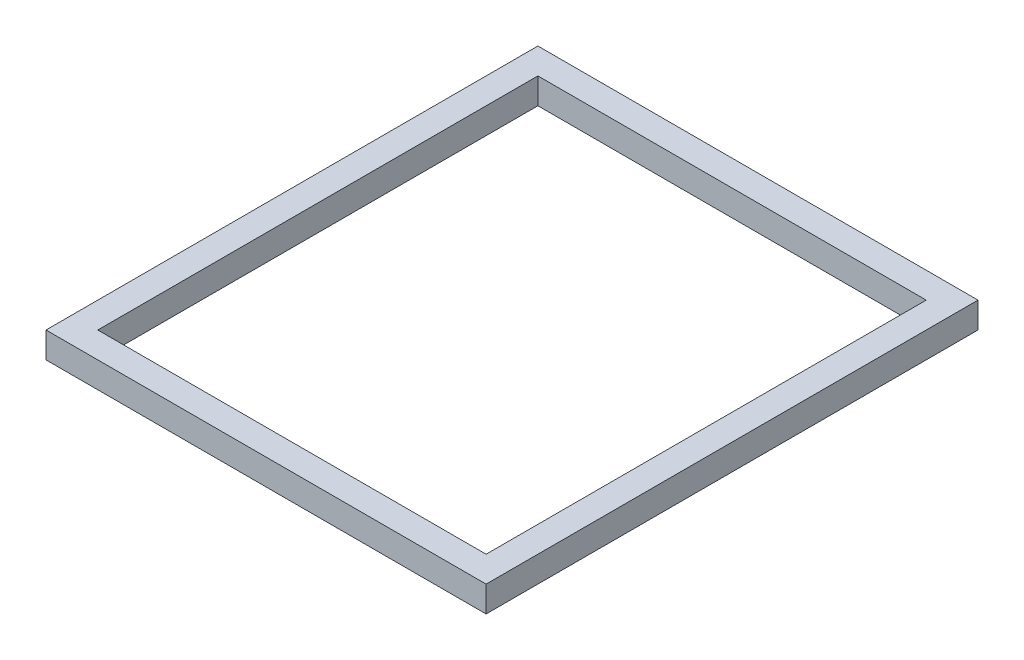
SolidWorks part; units mm, degrees
ref_plane "Front Plane" through (0, 0, 0) normal (0, 0, 1) x (1, 0, 0)
ref_plane "Top Plane" through (0, 0, 0) normal (0, 1, 0) x (1, 0, 0)
ref_plane "Right Plane" through (0, 0, 0) normal (1, 0, 0) x (0, 0, -1)
sketch "Sketch1" plane through (0, 0, 0) normal (0, 1, 0) x (1, 0, 0)
  line L1 (-53.975, -60.325) -> (53.975, -60.325)
  line L2 (-53.975, -60.325) -> (-53.975, 60.325)
  line L3 (-53.975, 60.325) -> (53.975, 60.325)
  line L4 (53.975, -60.325) -> (53.975, 60.325)
  line L5 (-53.975, -60.325) -> (53.975, 60.325) construction
  line L6 (-53.975, 60.325) -> (53.975, -60.325) construction
  line L7 (-47.625, -53.975) -> (47.625, -53.975)
  line L8 (-47.625, -53.975) -> (-47.625, 53.975)
  line L9 (-47.625, 53.975) -> (47.625, 53.975)
  line L10 (47.625, -53.975) -> (47.625, 53.975)
  line L11 (-47.625, -53.975) -> (47.625, 53.975) construction
  line L12 (-47.625, 53.975) -> (47.625, -53.975) construction
  point P0 (0, 0)
  point P5 (0, 0)
  dimension "D3" = 6.35
  dimension "D1" = 107.95
  dimension "D2" = 120.65
  dimension "D4" = 6.35
extrude "Boss-Extrude1" add sketch "Sketch1" along normal blind 6.35
